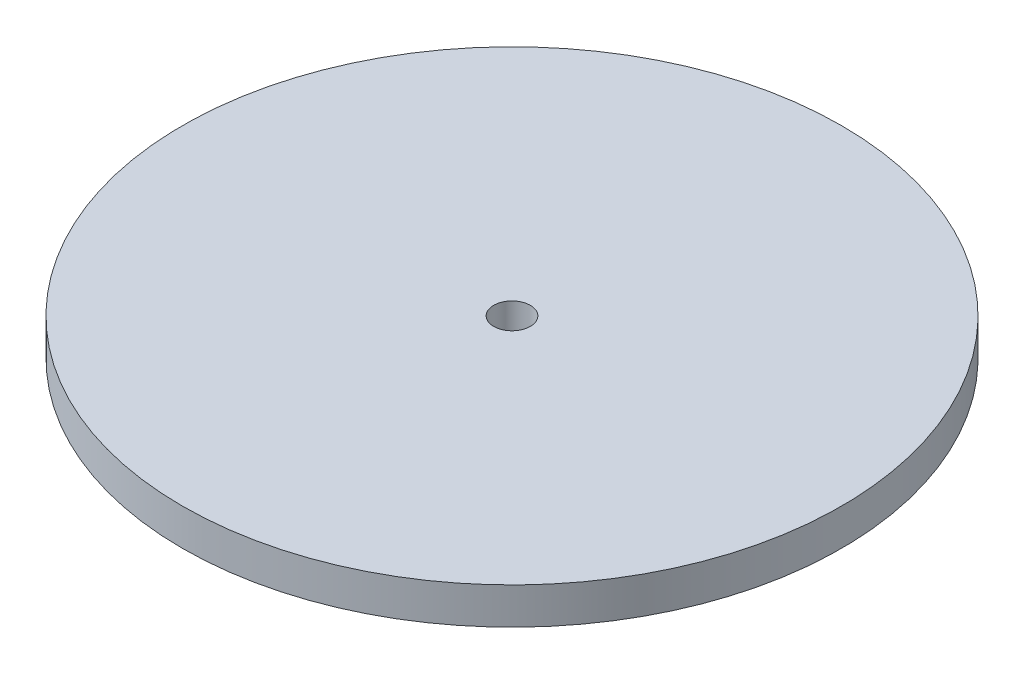
SolidWorks part; units mm, degrees
ref_plane "前视基准面" through (0, 0, 0) normal (0, 0, 1) x (1, 0, 0)
ref_plane "上视基准面" through (0, 0, 0) normal (0, 1, 0) x (1, 0, 0)
ref_plane "右视基准面" through (0, 0, 0) normal (1, 0, 0) x (0, 0, -1)
sketch "草图1" plane through (0, 0, 0) normal (0, 1, 0) x (1, 0, 0)
  circle A0 centre (0, 0) radius 90
  dimension "D1" = 180
extrude "凸台-拉伸1" add sketch "草图1" along normal blind 10 contours A0
sketch "草图2" plane through (0, 10, 0) normal (0, 1, 0) x (1, 0, 0)
  circle A0 centre (0, 0) radius 5
extrude "切除-拉伸1" cut sketch "草图2" against normal blind 10
